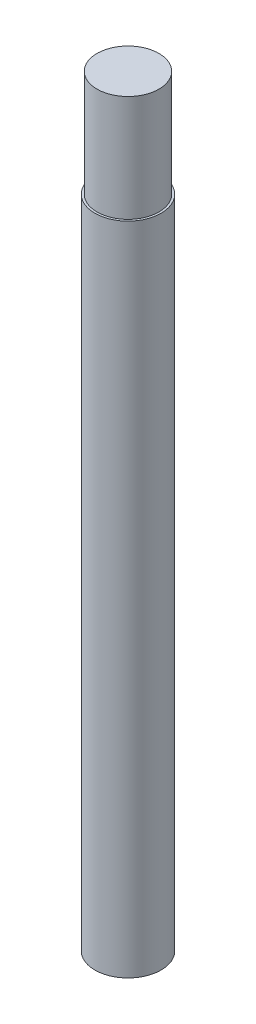
SolidWorks part; units mm, degrees
material "AISI 4130 Steel, normalized at 870C"
ref_plane "Front Plane" through (0, 0, 0) normal (0, 0, 1) x (1, 0, 0)
ref_plane "Top Plane" through (0, 0, 0) normal (0, 1, 0) x (1, 0, 0)
ref_plane "Right Plane" through (0, 0, 0) normal (1, 0, 0) x (0, 0, -1)
sketch "Sketch1" plane through (0, 0, 0) normal (0, 1, 0) x (1, 0, 0)
  circle A0 centre (0, 0) radius 7.8931
  dimension "D1" = 15.7861
extrude "Boss-Extrude1" add sketch "Sketch1" along normal blind 156.4386
sketch "Sketch2" plane through (0, 156.4386, 0) normal (0, 1, 0) x (1, 0, 0)
  circle A0 centre (0, 0) radius 7.3851
  circle A1 centre (0, 0) radius 7.8931 construction
  dimension "D1" = 0.508
extrude "Boss-Extrude2" add sketch "Sketch2" along normal blind 25.4
